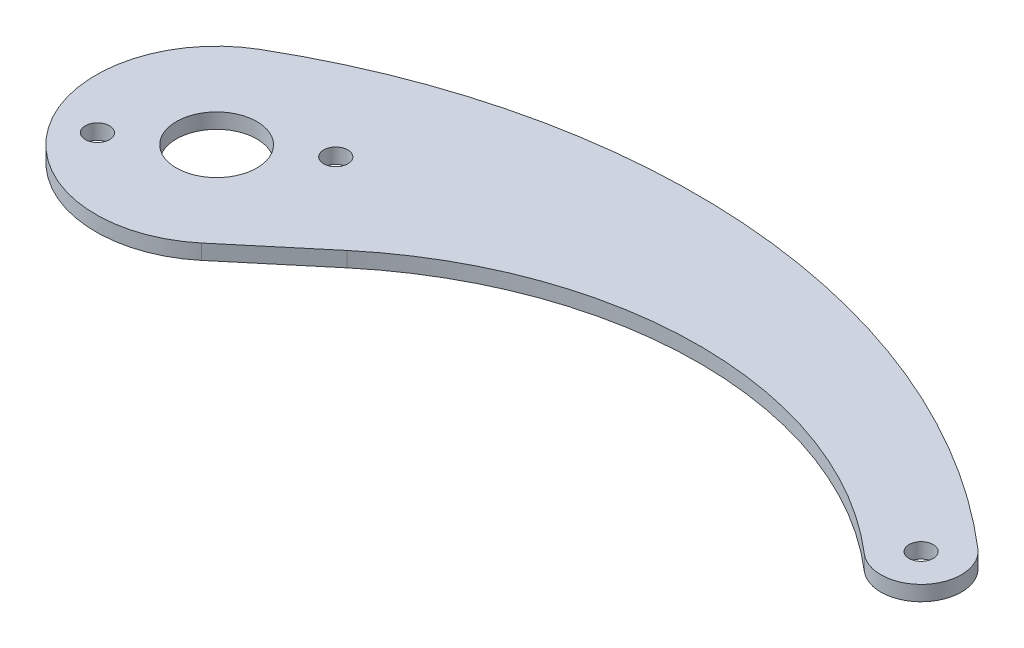
SolidWorks part; units mm, degrees
ref_plane "Plan de face" through (0, 0, 0) normal (0, 0, 1) x (1, 0, 0)
ref_plane "Plan de dessus" through (0, 0, 0) normal (0, 1, 0) x (1, 0, 0)
ref_plane "Plan de droite" through (0, 0, 0) normal (1, 0, 0) x (0, 0, -1)
sketch "Esquisse1" plane through (0, 0, 0) normal (0, 1, 0) x (1, 0, 0)
  line L0 (7.7027, -9.2015) -> (15.56, -2.6241)
  line L1 (72.6149, 3.0269) -> (67.3851, -3.0269) construction
  circle A0 centre (0, 0) radius 4
  circle A1 centre (70, 0) radius 1.2
  arc A2 (72.6149, 3.0269) -> (-6.0262, 10.3772) centre (28.139, -48.4559) ccw
  arc A4 (67.3851, -3.0269) -> (15.56, -2.6241) centre (41.2357, -33.2959) ccw
  arc A5 (67.3851, -3.0269) -> (72.6149, 3.0269) centre (70, 0) ccw
  arc A6 (-6.0262, 10.3772) -> (7.7027, -9.2015) centre (0, 0) ccw
  dimension "D1" = 2.4
  dimension "D2" = 4
  dimension "D3" = 8
  dimension "D4" = 70
  dimension "D5" = 12
  dimension "D6" = 40
  dimension "D7" = 53
extrude "Boss.-Extru.1" add sketch "Esquisse1" along normal blind 1.5
sketch "Esquisse2" plane through (0, 1.5, 0) normal (0, 1, 0) x (1, 0, 0)
  line L0 (-6.9595, -4.8801) -> (6.9595, 4.8801) construction
  circle A0 centre (-6.9595, -4.8801) radius 1.2
  circle A1 centre (6.9595, 4.8801) radius 1.2
  arc A2 (-6.0262, 10.3772) -> (7.7027, -9.2015) centre (0, 0) ccw construction
  point P7 (-9.8252, -6.8896)
  dimension "D1" = 17
  dimension "D2" = 2.4
extrude "Enlèv. mat.-Extru.1" cut sketch "Esquisse2" against normal through all
